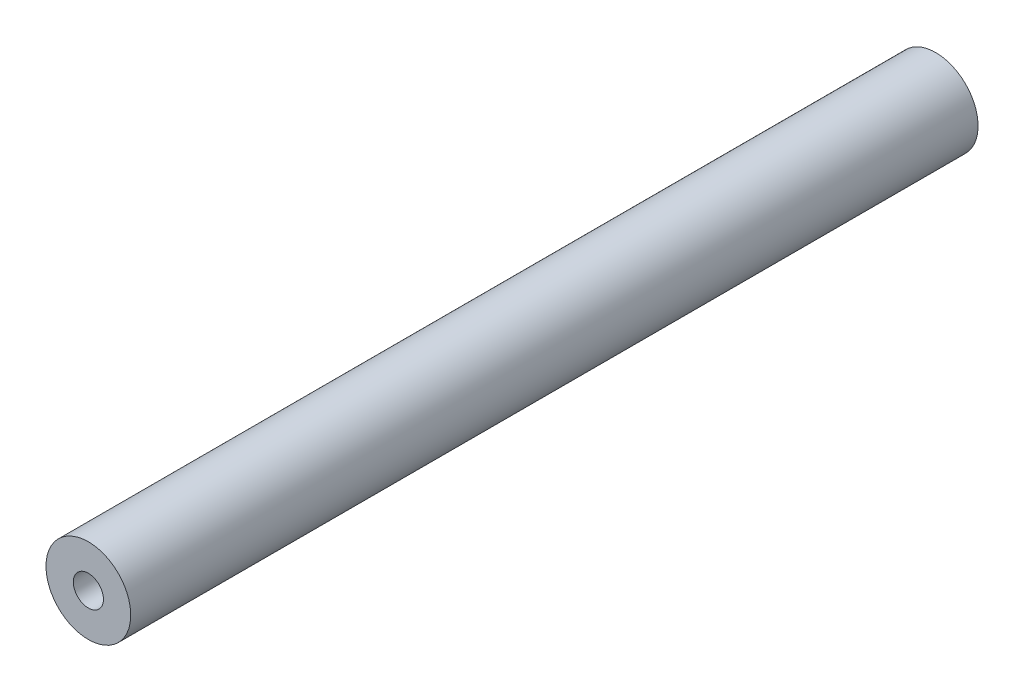
SolidWorks part; units mm, degrees
ref_plane "Ebene vorne" through (0, 0, 0) normal (0, 0, 1) x (1, 0, 0)
ref_plane "Ebene oben" through (0, 0, 0) normal (0, 1, 0) x (1, 0, 0)
ref_plane "Ebene rechts" through (0, 0, 0) normal (1, 0, 0) x (0, 0, -1)
sketch "Skizze1" plane through (0, 0, 0) normal (0, 0, 1) x (1, 0, 0)
  circle A0 centre (0, 0) radius 4.5
  dimension "D1" = 9
extrude "Aufsatz-Linear austragen1" add sketch "Skizze1" along normal blind 90
sketch "Skizze3" plane through (0, 0, 90) normal (0, 0, 1) x (1, 0, 0)
  circle A0 centre (0, 0) radius 1.6
  dimension "D1" = 3.2
extrude "Schnitt-Linear austragen1" cut sketch "Skizze3" against normal blind 4.5
sketch "Skizze4" plane through (0, 0, 0) normal (0, 0, -1) x (-1, 0, 0)
  circle A0 centre (0, 0) radius 1.6
  dimension "D1" = 3.2
extrude "Schnitt-Linear austragen2" cut sketch "Skizze4" against normal blind 4.5
